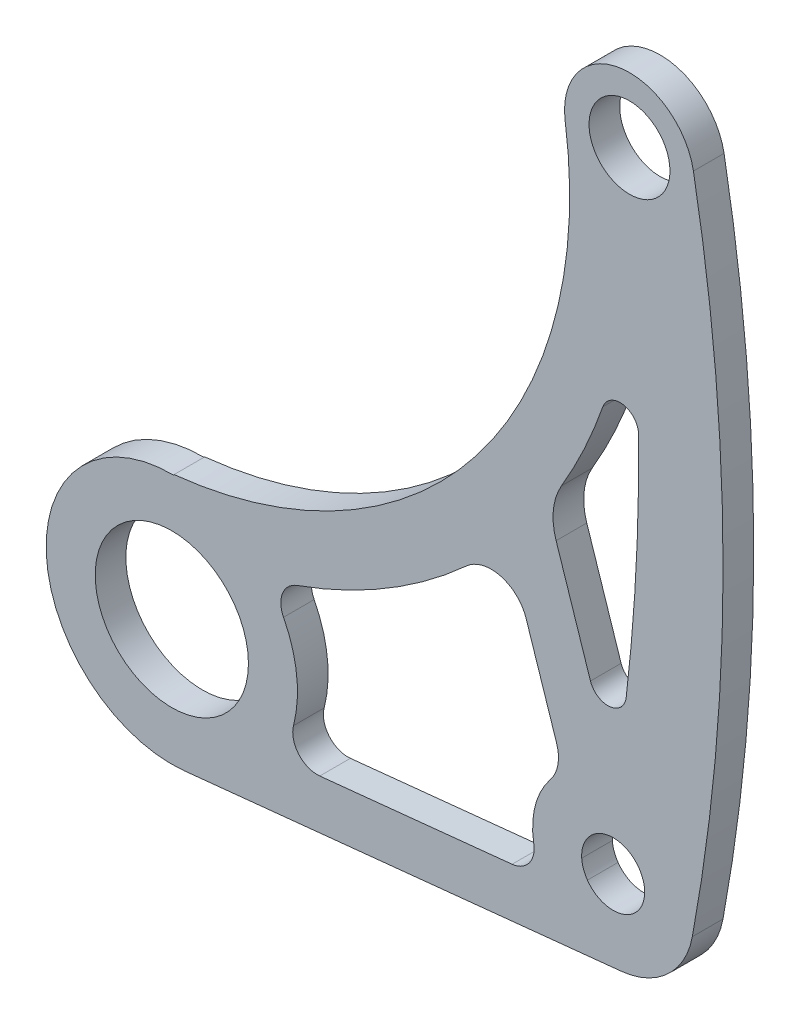
SolidWorks part; units mm, degrees
material "6061-T6 (SS)"
ref_plane "Front Plane" through (0, 0, 0) normal (0, 0, 1) x (1, 0, 0)
ref_plane "Top Plane" through (0, 0, 0) normal (0, 1, 0) x (1, 0, 0)
ref_plane "Right Plane" through (0, 0, 0) normal (1, 0, 0) x (0, 0, -1)
sketch "Sketch2" plane through (0, 0, 0) normal (0, 0, 1) x (1, 0, 0)
  line L0 (0, 0) -> (45.72, 0) construction
  line L1 (45.72, 0) -> (47.4133, 66.0183) construction
  line L2 (47.4133, 66.0183) -> (0, 0) construction
  line L3 (-9.9543, 8.3886) -> (42.2663, 70.3558)
  line L4 (54.1443, 66.0101) -> (54.0639, -0.0102)
  line L5 (46.5729, -8.3002) -> (1.3307, -12.9493)
  line L6 (-6.2268, 4.9225) -> (44.1256, 68.6173)
  line L7 (0.8114, -7.8959) -> (46.0536, -3.2468)
  line L8 (48.9813, -0.1295) -> (51.601, 65.852)
  line L10 (45.72, 0) -> (38.8832, 9.7026) construction
  line L11 (45.72, 0) -> (42.0108, 11.275) construction
  line L12 (45.72, 0) -> (44.9726, 11.8459) construction
  line L13 (47.2407, 59.2895) -> (45.9339, 8.3412)
  line L14 (45.72, 0) -> (36.8585, 26.9366) construction
  line L15 (34.7499, 24.3546) -> (40.5957, 6.585)
  line L16 (38.8824, 29.7758) -> (45.9339, 8.3412)
  line L17 (41.2892, 13.4683) -> (38.6201, 12.5902) construction
  line L18 (41.2892, 13.4683) -> (43.9584, 14.3464) construction
  circle A0 centre (0, 0) radius 7.9375
  circle A1 centre (45.72, 0) radius 3.2639
  circle A2 centre (47.4133, 66.0183) radius 4.191
  circle A3 centre (0, 0) radius 13.0175
  circle A4 centre (45.72, 0) radius 8.3439
  circle A5 centre (47.4133, 66.0183) radius 6.731
  circle A8 centre (-4.5053, 58.5645) radius 45.72
  circle A9 centre (-4.5053, 58.5645) radius 52.07
  circle A10 centre (-133.3933, 33.155) radius 190.5
  circle A11 centre (-142.1385, 38.656) radius 190.5
  point P24 (-129.0471, -12.9493)
  point P29 (47.2407, 59.2895)
  point P30 (45.72, 0)
  dimension "D1" = 8.382
  dimension "D2" = 6.5278
  dimension "D3" = 15.875
  dimension "D13" = 381
  dimension "D14" = 381
  dimension "2.7" = 45.72
  dimension "D5" = 66.04
  dimension "D6" = 5.08
  dimension "D7" = 2.54
  dimension "D8" = 5.08
  dimension "D9" = 81.28
  dimension "D4" = 54.83
  dimension "D10" = 71.79
  dimension "D11" = 86.39
  dimension "D12" = 6.35
extrude "Boss-Extrude1" add sketch "Sketch2" along normal blind 3.175 contours A3 A9 L13 A5 L6 A8 | A4 A10 A5 L4 | A5 L8 A4 L4 | A11 A4 L8 A5 A9 | A11 A9 A5 | A9 A11 L13 | A9 A5 L8 A2 | A11 A5 A9 A2 | A9 A2 L8 A5 | A2 A11 A5 L6 | A11 A2 A9 A5 | A5 A11 A2 L6 | L6 A9 A0 A3 | A3 A9 L6 | A9 A3 L7 A0 L6 | A9 L6 A0 | A9 A0 L7 A3 | L5 A11 A4 L7 A3 | A11 L5 A4 | A11 A4 L8 A1 L7 | A4 A11 L7 | L7 A11 A1 A4 | A11 L7 A1 | A11 A1 L8 A4 | A8 L6 A5 | A9 L15 A4 L16
ref_plane "Plane2" through (45.72, 0, 0) normal (-0.576, 0.8174, 0) x (0.8174, 0.576, 0)
split line "Split Line2"
ref_plane "Plane3" through (45.72, 0, 0) normal (-0.063, 0.998, 0) x (0.998, 0.063, 0)
split line "Split Line3"
fillet "Fillet1" radius 2.54 3 edges at (11.0749, -6.8412, 1.5875) (38.4148, -4.0318, 1.5875) (9.8489, 8.5121, 1.5875)
fillet "Fillet2" radius 3.81 2 edges at (40.5957, 6.585, 1.5875) (34.7499, 24.3546, 1.5875)
fillet "Fillet3" radius 1.905 2 edges at (45.9339, 8.3412, 1.5875) (47.5238, 56.5014, 1.5875)
fillet "Fillet4" radius 6.35 1 edges at (38.8824, 29.7758, 1.5875)
equation "\"Droop angle\"= 54.83"
equation "\"Static angle\"= 71.79"
equation "\"Jounce angle\"= 86.39"
equation "\"D4@Sketch2\"=\"Droop angle\""
equation "\"D10@Sketch2\"=\"Static angle\""
equation "\"D11@Sketch2\"=\"Jounce angle\""
